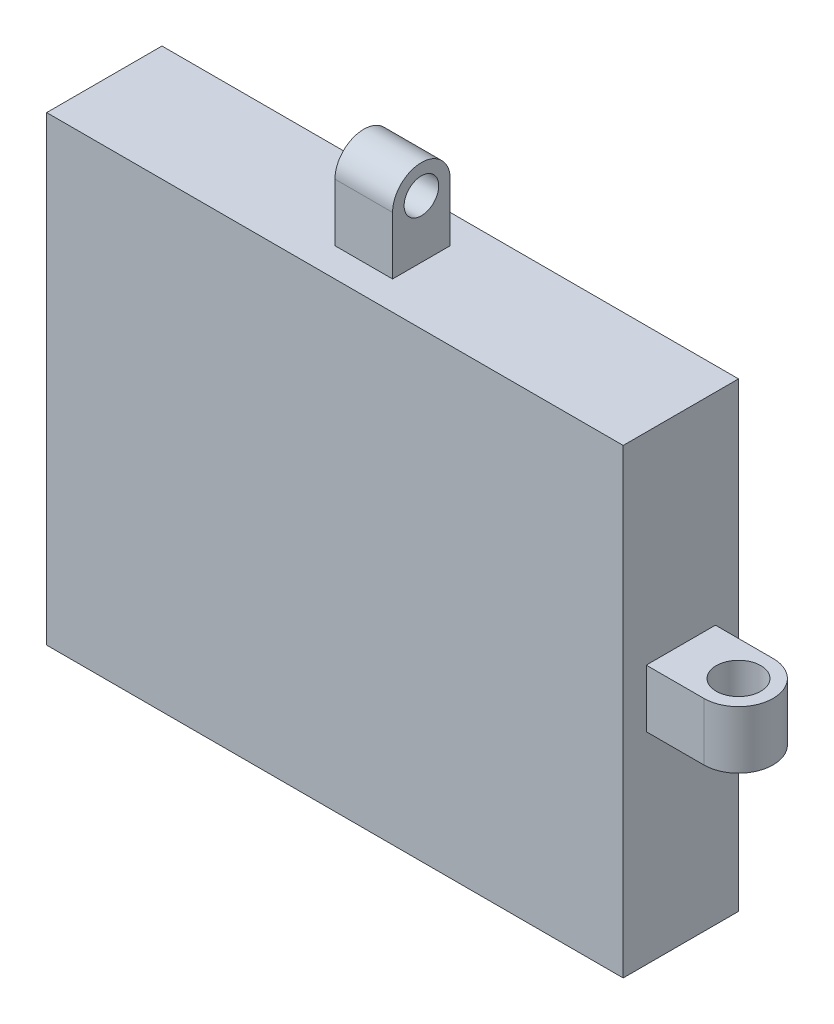
SolidWorks part; units mm, degrees
ref_plane "Front Plane" through (0, 0, 0) normal (0, 0, 1) x (1, 0, 0)
ref_plane "Top Plane" through (0, 0, 0) normal (0, 1, 0) x (1, 0, 0)
ref_plane "Right Plane" through (0, 0, 0) normal (1, 0, 0) x (0, 0, -1)
sketch "Sketch1" plane through (669.8418, 0, 0) normal (0, 0, 1) x (1, 0, 0)
  line L1 (-696.3103, 457.6379) -> (-646.3103, 457.6379)
  line L2 (-696.3103, 457.6379) -> (-696.3103, 417.6379)
  line L3 (-696.3103, 417.6379) -> (-646.3103, 417.6379)
  line L4 (-646.3103, 457.6379) -> (-646.3103, 417.6379)
  dimension "50" = 50
  dimension "D2" = 40
extrude "Boss-Extrude1" add sketch "Sketch1" along normal blind 10
sketch "Sketch5" plane through (23.5315, 0, 0) normal (1, 0, 0) x (0, 0, -1)
  line L0 (0, 417.6379) -> (0, 457.6379) construction
  line L1 (-8, 445.1379) -> (-2, 445.1379)
  line L2 (-8, 445.1379) -> (-8, 440.1379)
  line L3 (-8, 440.1379) -> (-2, 440.1379)
  line L4 (-2, 445.1379) -> (-2, 440.1379)
  line L5 (-8, 435.1379) -> (-2, 435.1379)
  line L6 (-8, 435.1379) -> (-8, 430.1379)
  line L7 (-8, 430.1379) -> (-2, 430.1379)
  line L8 (-2, 435.1379) -> (-2, 430.1379)
  line L9 (-10, 417.6379) -> (-10, 457.6379) construction
  line L10 (0, 437.6379) -> (-10, 437.6379)
  line L11 (-2, 440.1379) -> (-2, 437.6379)
  line L12 (-8, 435.1379) -> (-8, 437.6379)
  dimension "D1" = 5
  dimension "D2" = 2
  dimension "D3" = 2
  dimension "D4" = 2
  dimension "D5" = 2
  dimension "D6" = 5
  dimension "D7" = 5
extrude "Boss-Extrude3" add sketch "Sketch5" along normal blind 10 contours L4 L1 L2 L3 | L8 L5 L6 L7
sketch "Sketch6" plane through (669.8418, 445.1379, 0) normal (0, 1, 0) x (1, 0, 0)
  line L1 (-646.3103, -8) -> (-646.3103, -2) construction
  line L2 (-646.3103, -5) -> (-636.3103, -5) construction
  line L3 (-636.3103, -8) -> (-636.3103, -2) construction
  line L4 (-641.3103, -8) -> (-641.3103, -2) construction
  line L5 (-636.3103, -8) -> (-646.3103, -8) construction
  line L6 (-636.3103, -2) -> (-646.3103, -2) construction
  circle A1 centre (-641.3103, -5) radius 2
extrude "Cut-Extrude1" cut sketch "Sketch6" against normal blind 20
sketch "Sketch8" plane through (-26.4685, 0, 0) normal (-1, 0, 0) x (0, 0, 1)
  line L1 (0, 417.6379) -> (10, 417.6379)
  line L2 (0, 417.6379) -> (0, 457.6379)
  line L3 (0, 457.6379) -> (10, 457.6379)
  line L4 (10, 417.6379) -> (10, 457.6379)
extrude "Cut-Extrude2" cut sketch "Sketch8" against normal blind 25
sketch "Sketch9" plane through (0, 435.1379, 0) normal (0, 1, 0) x (1, 0, 0)
  line L1 (23.5315, -8) -> (33.5315, -8)
  line L2 (23.5315, -8) -> (23.5315, -2)
  line L3 (23.5315, -2) -> (33.5315, -2)
  line L4 (33.5315, -8) -> (33.5315, -2)
  circle A0 centre (28.5315, -5) radius 1.9309
extrude "Boss-Extrude4" add sketch "Sketch9" along normal blind 5
sketch "Sketch10" plane through (0, 0, 8) normal (0, 0, 1) x (1, 0, 0)
  line L0 (23.5315, 417.6379) -> (23.5315, 457.6379) construction
  line L1 (33.5315, 430.1379) -> (23.5315, 430.1379)
  line L2 (33.5315, 430.1379) -> (33.5315, 435.1379)
  line L3 (33.5315, 435.1379) -> (23.5315, 435.1379)
  line L4 (23.5315, 430.1379) -> (23.5315, 435.1379)
  line L6 (33.5315, 445.1379) -> (23.5315, 445.1379)
  line L7 (33.5315, 445.1379) -> (33.5315, 440.1379)
  line L8 (33.5315, 440.1379) -> (23.5315, 440.1379)
  line L9 (23.5315, 445.1379) -> (23.5315, 440.1379)
  dimension "D1" = 5
  dimension "D2" = 5
extrude "Cut-Extrude3" cut sketch "Sketch10" against normal blind 15 contours L7 L6 L9 L8 | L2 L1 L4 L3
mirror "Mirror1" about plane through (-1.4685, 0, 0) normal (1, 0, 0) of "Boss-Extrude1"
sketch "Sketch11" plane through (0, 457.6379, 0) normal (0, 1, 0) x (1, 0, 0)
  line L0 (23.5315, 0) -> (-26.4685, 0) construction
  line L1 (-3.9685, -2.5) -> (1.0315, -2.5)
  line L2 (-3.9685, -2.5) -> (-3.9685, -7.5)
  line L3 (-3.9685, -7.5) -> (1.0315, -7.5)
  line L4 (1.0315, -2.5) -> (1.0315, -7.5)
  line L5 (23.5315, -10) -> (-26.4685, -10) construction
  line L6 (23.5315, -10) -> (23.5315, 0) construction
  line L7 (-26.4685, -10) -> (-26.4685, 0) construction
  dimension "D1" = 2.5
  dimension "D2" = 2.5
  dimension "D3" = 22.5
  dimension "D4" = 22.5
extrude "Boss-Extrude5" add sketch "Sketch11" along normal blind 10
sketch "Sketch12" plane through (1.0315, 0, 0) normal (1, 0, 0) x (0, 0, -1)
  line L0 (-5, 467.6379) -> (-5, 457.6379) construction
  line L1 (-7.5, 467.6379) -> (-2.5, 467.6379) construction
  line L2 (-7.5, 457.6379) -> (-2.5, 457.6379) construction
  line L3 (-2.5, 462.6379) -> (-7.5, 462.6379) construction
  line L4 (-2.5, 467.6379) -> (-2.5, 457.6379) construction
  line L5 (-7.5, 467.6379) -> (-7.5, 457.6379) construction
  circle A1 centre (-5, 462.6379) radius 1.5
  dimension "D1" = 3
extrude "Cut-Extrude4" cut sketch "Sketch12" against normal blind 10
sketch "Sketch13" plane through (1.0315, 0, 0) normal (1, 0, 0) x (0, 0, -1)
  line L0 (-7.5, 462.6379) -> (-7.5, 467.6379)
  line L1 (-7.5, 467.6379) -> (-2.5, 467.6379)
  line L2 (-2.5, 467.6379) -> (-2.5, 457.6379) construction
  line L3 (-7.5, 467.6379) -> (-2.5, 467.6379) construction
  line L4 (-2.5, 467.6379) -> (-2.5, 462.6379)
  circle A0 centre (-5, 462.6379) radius 2.5
  line M3 (-2.5, 457.6379) -> (-2.5, 467.6379)
  line M4 (-2.5, 467.6379) -> (-7.5, 467.6379)
  line M5 (-7.5, 467.6379) -> (-7.5, 457.6379)
extrude "Cut-Extrude5" cut sketch "Sketch13" against normal blind 10 contours A0 M3 M4 M5
sketch "Sketch14" plane through (0, 440.1379, 0) normal (0, 1, 0) x (1, 0, 0)
  line L0 (28.5315, -2) -> (33.5315, -2)
  line L1 (28.5315, -8) -> (33.5315, -8)
  circle A0 centre (28.5315, -5) radius 3
  line M6 (23.5315, -8) -> (33.5315, -8)
  line M7 (33.5315, -8) -> (33.5315, -2)
  line M8 (33.5315, -2) -> (23.5315, -2)
extrude "Cut-Extrude6" cut sketch "Sketch14" against normal blind 10 contours A0 M6 M7 M8
